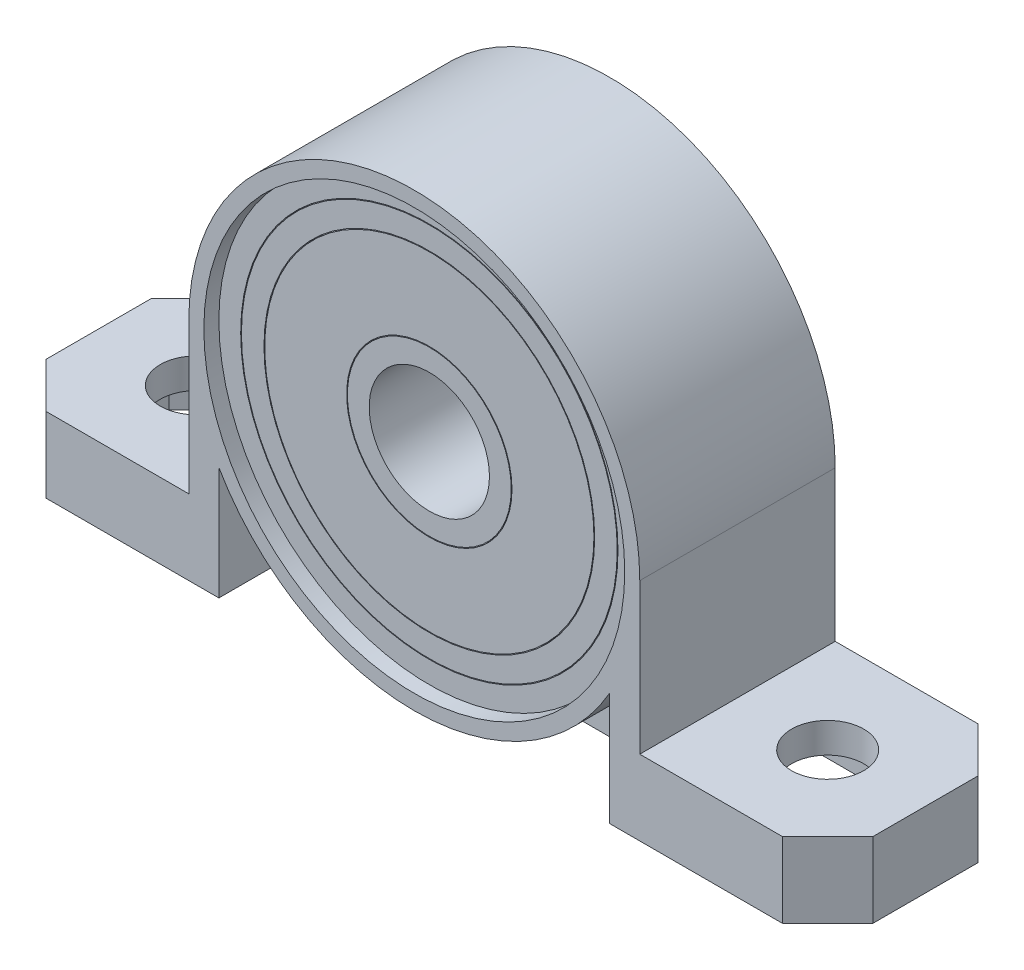
SolidWorks part; units mm, degrees
material "1345 Alloy"
ref_plane "前视基准面" through (0, 0, 0) normal (0, 0, 1) x (1, 0, 0)
ref_plane "上视基准面" through (0, 0, 0) normal (0, 1, 0) x (1, 0, 0)
ref_plane "右视基准面" through (0, 0, 0) normal (1, 0, 0) x (0, 0, -1)
sketch "Sketch1" plane through (0, 0, 0) normal (0, 1, 0) x (1, 0, 0)
  line L0 (0, -3) -> (0, -10)
  line L1 (3, -13) -> (52, -13)
  line L2 (55, -10) -> (55, -3)
  line L3 (52, 0) -> (3, 0)
  line L4 (3, 0) -> (0, -3)
  line L5 (0, -10) -> (3, -13)
  line L6 (52, -13) -> (55, -10)
  line L7 (55, -3) -> (52, 0)
  point P0 (0, 0)
  point P1 (0, -13)
  point P4 (55, -13)
  point P5 (55, 0)
  dimension "D1" = 13
  dimension "D2" = 55
extrude "Boss-Extrude1" add sketch "Sketch1" along normal blind 5
sketch "Sketch2" plane through (0, 0, 13) normal (0, 0, 1) x (1, 0, 0)
  line L0 (27.5, -4.7629) -> (27.5, 63.8869) construction
  line L1 (-9.8647, 0) -> (67.9675, 0) construction
  line L2 (0, 5) -> (0, 0) construction
  line L3 (-9.8647, 15) -> (67.9675, 15) construction
  line L4 (12.5, 15) -> (12.5, 0)
  line L5 (12.5, 0) -> (42.5, 0)
  line L6 (42.5, 0) -> (42.5, 15)
  arc A0 (42.5, 15) -> (12.5, 15) centre (27.5, 15) ccw
  dimension "D3" = 30
  dimension "D1" = 27.5
  dimension "D2" = 15
extrude "Boss-Extrude2" add sketch "Sketch2" against normal blind 13
sketch "Sketch3" plane through (0, 0, 13) normal (0, 0, 1) x (1, 0, 0)
  line L0 (27.5, 32.956) -> (27.5, -5.7155) construction
  line L1 (14.5, 7.5167) -> (14.5, 0)
  line L2 (40.5, 7.5167) -> (40.5, 0)
  line L4 (14.5, 0) -> (14.5, -1)
  line L5 (14.5, 32.956) -> (14.5, -5.7155) construction
  line L6 (40.5, 32.956) -> (40.5, -5.7155) construction
  line L7 (14.5, -1) -> (40.5, -1)
  line L8 (40.5, -1) -> (40.5, 0)
  line L9 (3, 0) -> (52, 0) construction
  arc A0 (14.5, 7.5167) -> (40.5, 7.5167) centre (27.5, 15) ccw
  dimension "D1" = 30
  dimension "D4" = 1
  dimension "D5" = 1
  dimension "D2" = 13
  dimension "D3" = 13
extrude "Cut-Extrude1" cut sketch "Sketch3" against normal blind 5
sketch "Sketch4" plane through (0, 0, 0) normal (0, 0, -1) x (-1, 0, 0)
  line L0 (-27.5, 35.6005) -> (-27.5, -5.3705) construction
  line L1 (-40.5, 7.5167) -> (-40.5, -2.1511)
  line L2 (-14.5, 7.5167) -> (-14.5, -2.1511)
  line L3 (-40.5, -2.1511) -> (-14.5, -2.1511)
  line L5 (-40.5, 35.6005) -> (-40.5, -5.3705) construction
  line L6 (-14.5, 35.6005) -> (-14.5, -5.3705) construction
  arc A0 (-40.5, 7.5167) -> (-14.5, 7.5167) centre (-27.5, 15) ccw
  dimension "D1" = 30
  dimension "D2" = 13
  dimension "D3" = 13
extrude "Cut-Extrude2" cut sketch "Sketch4" against normal blind 5
sketch "Sketch5" plane through (0, 0, 0) normal (0, -1, 0) x (1, 0, 0)
  line L0 (27.5, 14.721) -> (27.5, -1.8743) construction
  line L1 (0, 3) -> (0, 10) construction
  line L2 (6.5, 14.721) -> (6.5, -1.8743) construction
  line L3 (48.5, 14.721) -> (48.5, -1.8743) construction
  line L4 (-2.0881, 6.5) -> (57.1647, 6.5) construction
  line L5 (3, 13) -> (14.5, 13) construction
  circle A0 centre (6.5, 6.5) radius 2.4
  circle A1 centre (48.5, 6.5) radius 2.4
  dimension "D5" = 4.8
  dimension "D1" = 27.5
  dimension "D4" = 6.5
  dimension "D2" = 21
  dimension "D3" = 21
extrude "Cut-Extrude3" cut sketch "Sketch5" against normal through all
sketch "Sketch6" plane through (0, 0, 0) normal (0, -1, 0) x (1, 0, 0)
  line L0 (14.5, 13) -> (3, 13) construction
  line L1 (3, 13) -> (0, 10) construction
  line L2 (0, 10) -> (0, 3) construction
  line L3 (0, 3) -> (3, 0) construction
  line L4 (3, 0) -> (14.5, 0) construction
  line L5 (14.5, 0) -> (14.5, 13) construction
  line L6 (27.5, 18.0441) -> (27.5, -5.4811) construction
  line L7 (12.5, 2) -> (12.5, 11)
  line L8 (12.5, 11) -> (3.8284, 11)
  line L9 (3.8284, 11) -> (2, 9.1716)
  line L10 (2, 9.1716) -> (2, 3.8284)
  line L11 (2, 3.8284) -> (3.8284, 2)
  line L12 (3.8284, 2) -> (12.5, 2)
  line L13 (51.1716, 2) -> (42.5, 2)
  line L14 (53, 3.8284) -> (51.1716, 2)
  line L15 (53, 9.1716) -> (53, 3.8284)
  line L16 (51.1716, 11) -> (53, 9.1716)
  line L17 (42.5, 11) -> (51.1716, 11)
  line L18 (42.5, 2) -> (42.5, 11)
  dimension "D1" = 27.5
  dimension "D2" = 2
extrude "Cut-Extrude4" cut sketch "Sketch6" against normal blind 3
sketch "Sketch7" plane through (0, 0, 13) normal (0, 0, 1) x (1, 0, 0)
  circle A0 centre (27.5, 15) radius 14
  dimension "D1" = 28
extrude "Cut-Extrude5" cut sketch "Sketch7" against normal blind 1
sketch "Sketch8" plane through (0, 0, 0) normal (0, 0, -1) x (-1, 0, 0)
  circle A0 centre (-27.5, 15) radius 14
  dimension "D1" = 28
extrude "Cut-Extrude6" cut sketch "Sketch8" against normal blind 1
sketch "Sketch9" plane through (0, 0, 12) normal (0, 0, 1) x (1, 0, 0)
  circle A0 centre (27.5, 15) radius 4
  dimension "D1" = 8
extrude "Cut-Extrude7" cut sketch "Sketch9" against normal through all
sketch "Sketch10" plane through (0, 0, 12) normal (0, 0, 1) x (1, 0, 0)
  circle A0 centre (27.5, 15) radius 12.55
  circle A1 centre (27.5, 15) radius 12.5
  dimension "D1" = 25.1
  dimension "D2" = 25
extrude "Cut-Extrude8" cut sketch "Sketch10" against normal blind 0.5
sketch "Sketch11" plane through (0, 0, 12) normal (0, 0, 1) x (1, 0, 0)
  circle A0 centre (27.5, 15) radius 11
  circle A1 centre (27.5, 15) radius 10.95
  dimension "D1" = 22
  dimension "D2" = 21.9
extrude "Cut-Extrude9" cut sketch "Sketch11" against normal blind 0.5
sketch "Sketch12" plane through (0, 0, 12) normal (0, 0, 1) x (1, 0, 0)
  circle A2 centre (27.5, 15) radius 5.45
  circle A3 centre (27.5, 15) radius 5.5
  dimension "D1" = 11
  dimension "D2" = 10.9
extrude "Cut-Extrude10" cut sketch "Sketch12" against normal blind 0.5
sketch "Sketch13" plane through (0, 0, 1) normal (0, 0, -1) x (-1, 0, 0)
  circle A0 centre (-27.5, 15) radius 5.5
  circle A1 centre (-27.5, 15) radius 5.45
  dimension "D1" = 11
  dimension "D2" = 10.9
extrude "Cut-Extrude11" cut sketch "Sketch13" against normal blind 0.5
sketch "Sketch14" plane through (0, 0, 1) normal (0, 0, -1) x (-1, 0, 0)
  circle A0 centre (-27.5, 15) radius 12.55
  circle A1 centre (-27.5, 15) radius 12.5
  dimension "D1" = 25
  dimension "D2" = 25.1
extrude "Cut-Extrude12" cut sketch "Sketch14" against normal blind 0.5
sketch "Sketch15" plane through (0, 0, 1) normal (0, 0, -1) x (-1, 0, 0)
  circle A0 centre (-27.5, 15) radius 10.95
  circle A1 centre (-27.5, 15) radius 11
  dimension "D1" = 22
  dimension "D2" = 21.9
extrude "Cut-Extrude13" cut sketch "Sketch15" against normal blind 0.5
